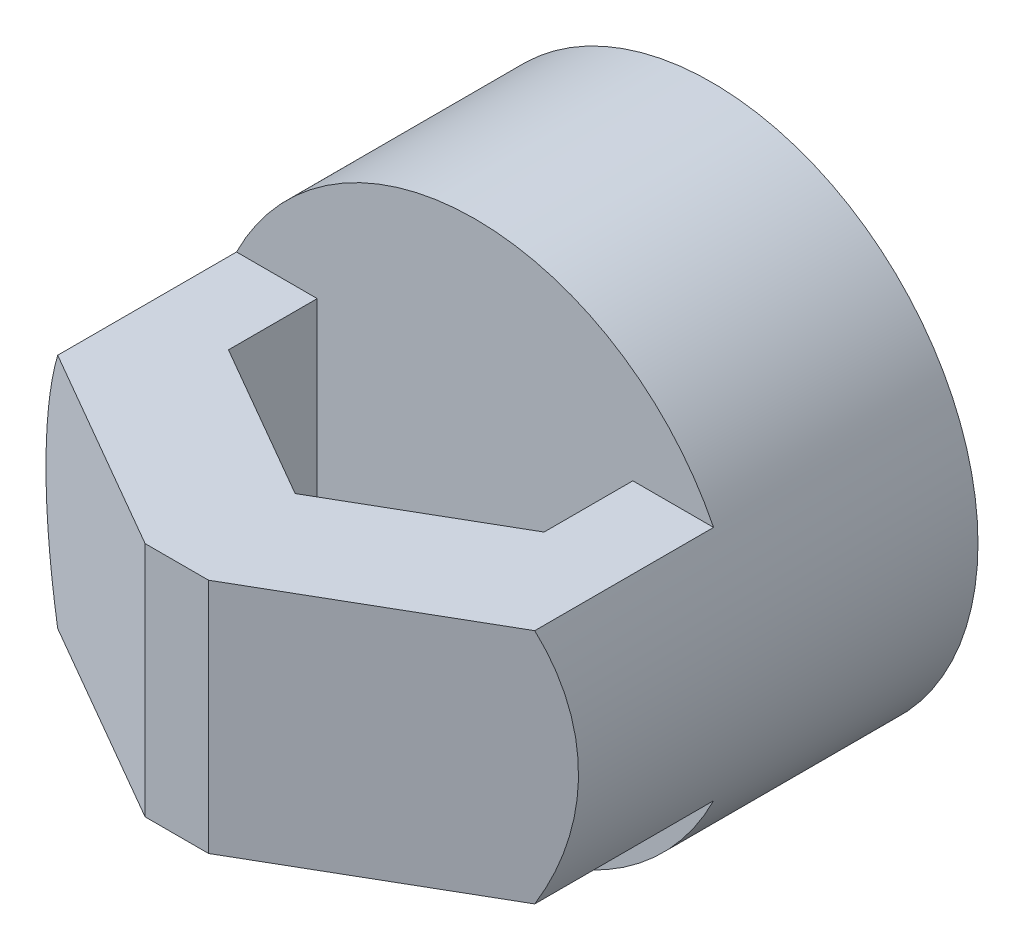
SolidWorks part; units mm, degrees
ref_plane "Front Plane" through (0, 0, 0) normal (0, 0, 1) x (1, 0, 0)
ref_plane "Top Plane" through (0, 0, 0) normal (0, 1, 0) x (1, 0, 0)
ref_plane "Right Plane" through (0, 0, 0) normal (1, 0, 0) x (0, 0, -1)
sketch "Sketch1" plane through (0, 0, 0) normal (0, 0, 1) x (1, 0, 0)
  circle A0 centre (0, 0) radius 5.5
  circle A1 centre (0, 0) radius 9
  dimension "D1" = 11
  dimension "D2" = 18
extrude "Boss-Extrude1" add sketch "Sketch1" along normal blind 5
sketch "Sketch2" plane through (0, 0, 5) normal (0, 0, 1) x (1, 0, 0)
  circle A0 centre (0, 0) radius 9 construction
  circle A1 centre (0, 0) radius 9
extrude "Boss-Extrude2" add sketch "Sketch2" along normal blind 3
sketch "Sketch3" plane through (0, 0, 0) normal (0, 1, 0) x (1, 0, 0)
  line L0 (-5.3337, -8) -> (-5.3337, -11)
  line L1 (-9, -8) -> (9, -8) construction
  line L2 (-5.3337, -11) -> (0, -14.0794)
  line L3 (0, -14.0794) -> (5.3337, -11)
  line L4 (5.3337, -11) -> (5.3337, -8)
  line L5 (5.3337, -8) -> (-5.3337, -8) construction
  line L6 (-5.3337, -11) -> (5.3337, -11) construction
  line L7 (9, -8) -> (9, -13.5021)
  line L8 (9, -13.5021) -> (1.0718, -18.0794)
  line L9 (1.0718, -18.0794) -> (-1.0718, -18.0794)
  line L10 (-1.0718, -18.0794) -> (-9, -13.5021)
  line L11 (-9, -13.5021) -> (-9, -8)
  line L12 (-9, -13.5021) -> (9, -13.5021) construction
  line L13 (-9, -8) -> (-5.3337, -8)
  line L14 (5.3337, -8) -> (9.084, -8)
  line L15 (0, 0) -> (0, -8) construction
  line L16 (0, -8) -> (0, -11) construction
  line L17 (0, -11) -> (0, -13.5021) construction
  line L18 (0, -13.5021) -> (0, -14.0794) construction
  line L19 (0, -18.0794) -> (0, -14.0794) construction
  dimension "D1" = 3.6663
  dimension "D2" = 4
  dimension "D3" = 30
  dimension "D4" = 3
  dimension "D5" = 4
extrude "Boss-Extrude3" add sketch "Sketch3" along normal mid plane 8 contours L14 L4 L3 L2 L0 L13 L11 L10 L9 L8 L7
sketch "Sketch4" plane through (0, 0, 8) normal (0, 0, 1) x (1, 0, 0)
  circle A0 centre (0, 0) radius 9
  circle A1 centre (0, 0) radius 9 construction
extrude "Cut-Extrude1" cut sketch "Sketch4" along normal through all flip side to cut
